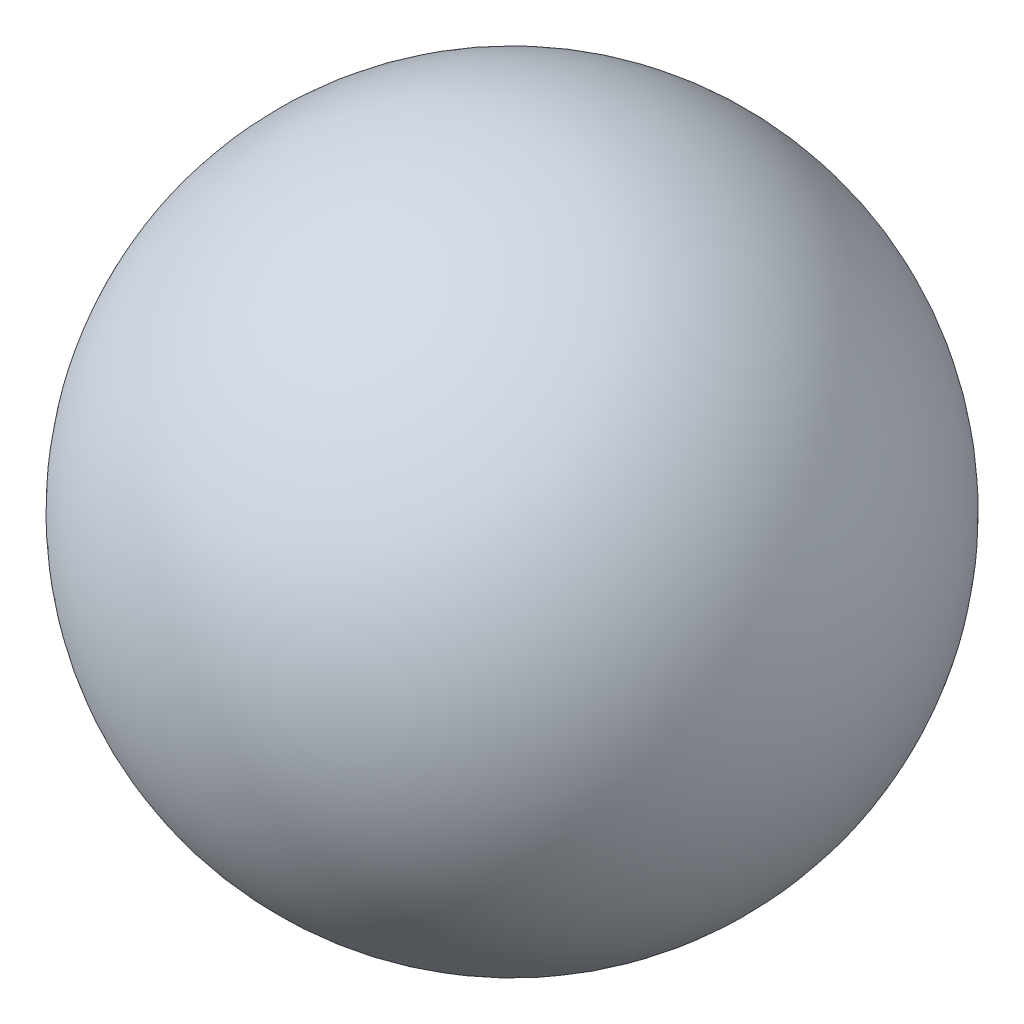
SolidWorks part; units mm, degrees
material "1060 Alloy"
ref_plane "Front Plane" through (0, 0, 0) normal (0, 0, 1) x (1, 0, 0)
ref_plane "Top Plane" through (0, 0, 0) normal (0, 1, 0) x (1, 0, 0)
ref_plane "Right Plane" through (0, 0, 0) normal (1, 0, 0) x (0, 0, -1)
sketch "Sketch1" plane through (0, 0, 0) normal (0, 0, 1) x (1, 0, 0)
  line L0 (0, 0) -> (2.2, 0)
  line L1 (0, 0) -> (-2.2, 0)
  arc A0 (2.2, 0) -> (-2.2, 0) centre (0, 0) ccw
  dimension "D1" = 4.4
revolve "Revolve1" add sketch "Sketch1" angle 360 about L1
scale "Scale1" bodies to scale 101 scale about centroid uniform scaling yes scale factor 6
scale "Scale2" scale about centroid uniform scaling yes scale factor 3.323882
scale "Scale3" [suppressed]
scale "Scale4" [suppressed]
scale "Scale5" [suppressed]
